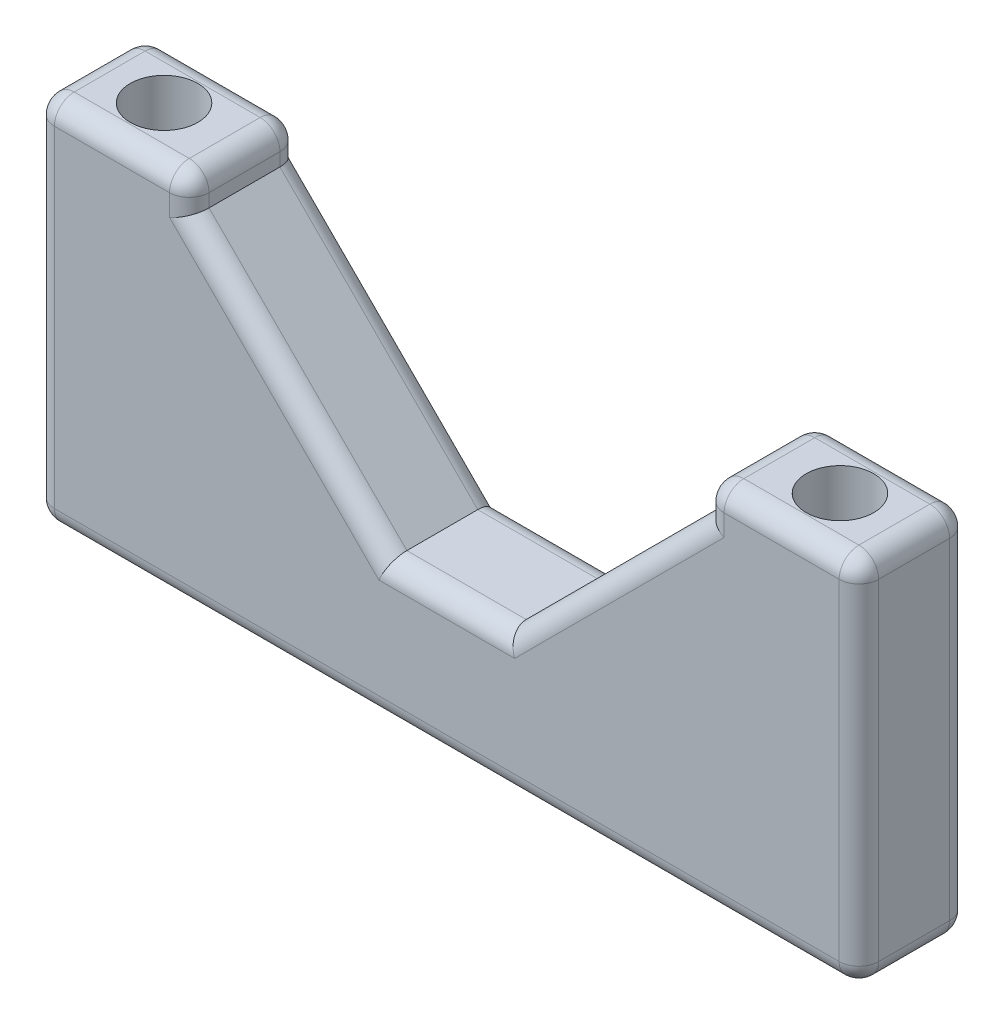
SolidWorks part; units mm, degrees
ref_plane "Front Plane" through (0, 0, 0) normal (0, 0, 1) x (1, 0, 0)
ref_plane "Top Plane" through (0, 0, 0) normal (0, 1, 0) x (1, 0, 0)
ref_plane "Right Plane" through (0, 0, 0) normal (1, 0, 0) x (0, 0, -1)
sketch "Sketch1" plane through (0, 0, 0) normal (0, 1, 0) x (1, 0, 0)
  line L0 (0, 0) -> (0, 4.9894) construction
  line L1 (-12.5, 0) -> (12.5, 0) construction
  line L2 (12.5, -1.675) -> (-12.5, -1.675)
  line L3 (12.5, -1.675) -> (12.5, 1.675)
  line L4 (12.5, 1.675) -> (-12.5, 1.675)
  line L5 (-12.5, -1.675) -> (-12.5, 1.675)
  line L6 (12.5, -1.675) -> (-12.5, 1.675) construction
  line L7 (12.5, 1.675) -> (-12.5, -1.675) construction
  circle A0 centre (-10.25, 0) radius 1.025
  circle A1 centre (10.25, 0) radius 1.025
  dimension "D3" = 2.05
  dimension "D1" = 20.5
  dimension "D2" = 25
  dimension "D4" = 3.35
extrude "Standoff Extrude" add sketch "Sketch1" along normal blind 11.24
sketch "Sketch2" plane through (0, 0, 1.675) normal (0, 0, 1) x (1, 0, 0)
  line L0 (-12.5, 11.24) -> (12.5, 11.24) construction
  line L1 (-7.81, 11.24) -> (7.81, 11.24)
  line L2 (-7.81, 11.24) -> (-7.81, 4.24)
  line L3 (-7.81, 4.24) -> (7.81, 4.24)
  line L4 (7.81, 11.24) -> (7.81, 4.24)
  line L5 (0, 0) -> (0, 11.24) construction
  dimension "D1" = 15.62
  dimension "D2" = 7
extrude "Standoff Cut" cut sketch "Sketch2" against normal through all
chamfer "Chamfer1" distance 6 angle 45 2 edges at (7.81, 4.24, 0) (-7.81, 4.24, 0)
fillet "Fillet2" radius 0.6 26 edges at (-12.5, 11.24, 0) (-12.5, 0, 0) (-12.5, 5.62, -1.675) (0, 0, -1.675) (12.5, 5.62, -1.675) (10.155, 11.24, -1.675) (7.81, 10.74, -1.675) (4.81, 7.24, -1.675) (0, 4.24, -1.675) (-4.81, 7.24, -1.675) (-7.81, 10.74, -1.675) (-10.155, 11.24, -1.675) (4.81, 7.24, 1.675) (7.81, 10.74, 1.675) (10.155, 11.24, 1.675) (12.5, 5.62, 1.675) (0, 0, 1.675) (-12.5, 5.62, 1.675) (-10.155, 11.24, 1.675) (-7.81, 10.74, 1.675) (-4.81, 7.24, 1.675) (0, 4.24, 1.675) (12.5, 0, 0) (12.5, 11.24, 0) (7.81, 11.24, 0) (-7.81, 11.24, 0)
equation "\"PLA_shrink\"=0.3mm"
equation "\"fit_sliding\"=0.5mm"
equation "\"fit_snap\"=0.3mm"
equation "\"fit_tight\"=0.2mm"
equation "\"m2_tap\"= 1.75mm + \"PLA_shrink\""
equation "\"m2_thin_wall\"= 1.9mm + \"PLA_shrink\""
equation "\"m2_standard\"= 2.2mm + \"PLA_shrink\""
equation "\"m2_head\"= 3.45mm + \"PLA_shrink\""
equation "\"m2.5_tap\"= 2.05 + \"PLA_shrink\""
equation "\"m2.5_standard\"= 2.75 + \"PLA_shrink\""
equation "\"m2.5_head\"= 5mm + \"PLA_shrink\""
equation "\"m3_tap\"= 2.5mm + \"PLA_shrink\""
equation "\"m3_standard\"= 3.3mm + \"PLA_shrink\""
equation "\"m3_head\"= 6mm + \"PLA_shrink\""
equation "\"connector_width\"= 9.35mm"
equation "\"wire_width\"= 3.1mm + \"PLA_shrink\""
equation "\"D3@Sketch1\"=\"m2_tap\""
